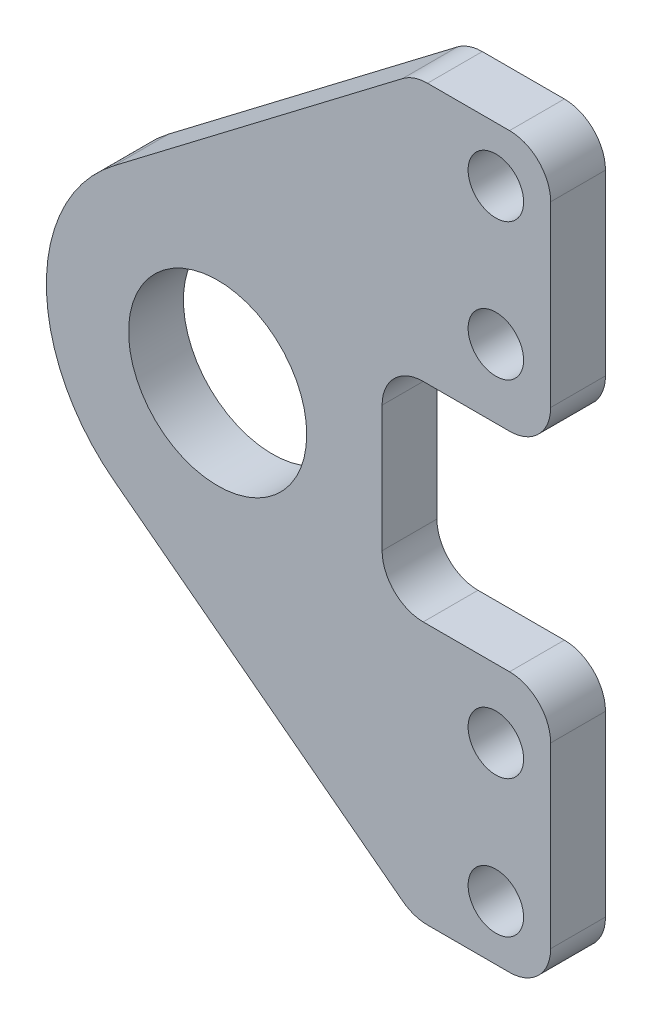
SolidWorks part; units mm, degrees
material "Thornel Mat VMA"
ref_plane "前视基准面" through (0, 0, 0) normal (0, 0, 1) x (1, 0, 0)
ref_plane "上视基准面" through (0, 0, 0) normal (0, 1, 0) x (1, 0, 0)
ref_plane "右视基准面" through (0, 0, 0) normal (1, 0, 0) x (0, 0, -1)
other "Configuration Table"
sketch "草图1" plane through (0, 0, 0) normal (0, 0, 1) x (1, 0, 0)
  line L0 (-7.5727, 9.9451) -> (14.3, 26.6)
  line L1 (14.3, 26.6) -> (24.3, 26.6)
  line L3 (14.3, -26.6) -> (24.3, -26.6)
  line L4 (24.3, 26.6) -> (24.3, -26.6)
  line L5 (-7.5727, -9.9451) -> (14.3, -26.6)
  circle A0 centre (0, 0) radius 6.5
  circle A1 centre (20.3, 22.6) radius 2.025
  circle A2 centre (20.3, 12.6) radius 2.025
  circle A3 centre (20.3, -12.6) radius 2.025
  circle A4 centre (20.3, -22.6) radius 2.025
  arc A5 (-7.5727, 9.9451) -> (-7.5727, -9.9451) centre (0, 0) ccw
  point P7 (24.3, 0)
  dimension "D1" = 4.05
  dimension "D7" = 13
  dimension "D11" = 25
  dimension "D2" = 24.3
  dimension "D3" = 4
  dimension "D4" = 10
  dimension "D5" = 10
  dimension "D6" = 25.2
  dimension "D8" = 12.6
  dimension "D9" = 4
  dimension "D12" = 10
extrude "凸台-拉伸1" add sketch "草图1" along normal mid plane 4
sketch "草图2" plane through (0, 0, 2) normal (0, 0, 1) x (1, 0, 0)
  line L0 (24.3, -26.6) -> (24.3, 26.6) construction
  line L1 (24.3, -7.6) -> (12, -7.6)
  line L2 (24.3, -7.6) -> (24.3, 7.6)
  line L3 (24.3, 7.6) -> (12, 7.6)
  line L4 (12, -7.6) -> (12, 7.6)
  circle A0 centre (0, 0) radius 12.5 construction
  circle A1 centre (20.3, -12.6) radius 2.025 construction
  circle A2 centre (0, 0) radius 6.5 construction
  point P6 (12, 0)
  dimension "D1" = 5
  dimension "D2" = 12
extrude "切除-拉伸1" cut sketch "草图2" against normal blind 10
fillet "圆角1" radius 3 8 edges at (24.3, 7.6, 0) (24.3, 26.6, 0) (14.3, 26.6, 0) (14.3, -26.6, 0) (24.3, -26.6, 0) (24.3, -7.6, 0) (12, -7.6, 0) (12, 7.6, 0)
